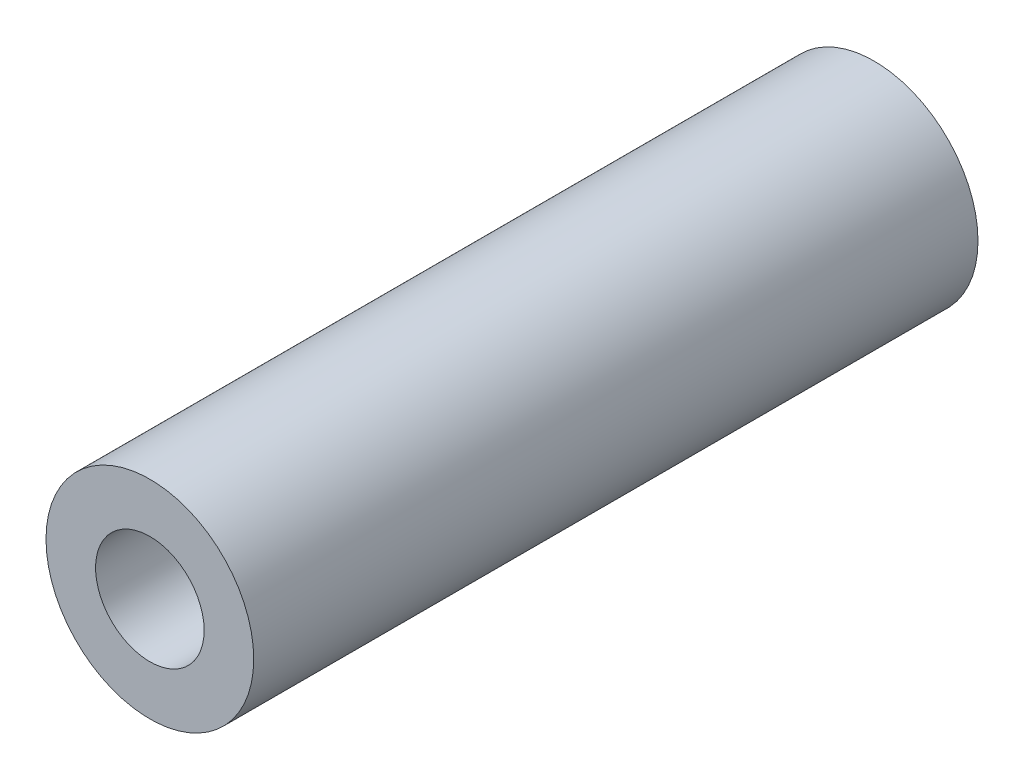
SolidWorks part; units mm, degrees
ref_plane "Front Plane" through (0, 0, 0) normal (0, 0, 1) x (1, 0, 0)
ref_plane "Top Plane" through (0, 0, 0) normal (0, 1, 0) x (1, 0, 0)
ref_plane "Right Plane" through (0, 0, 0) normal (1, 0, 0) x (0, 0, -1)
sketch "Sketch1" plane through (0, 0, 0) normal (0, 0, 1) x (1, 0, 0)
  circle A1 centre (0, 0) radius 4.7625
  dimension "D2" = 9.525
extrude "Boss-Extrude1" add sketch "Sketch1" along normal mid plane 33.2105
sketch "Sketch2" plane through (0, 0, 16.6053) normal (0, 0, 1) x (1, 0, 0)
  circle A0 centre (0, 0) radius 2.4892
  dimension "D1" = 4.9784
extrude "Cut-Extrude1" cut sketch "Sketch2" against normal through all contours A0
